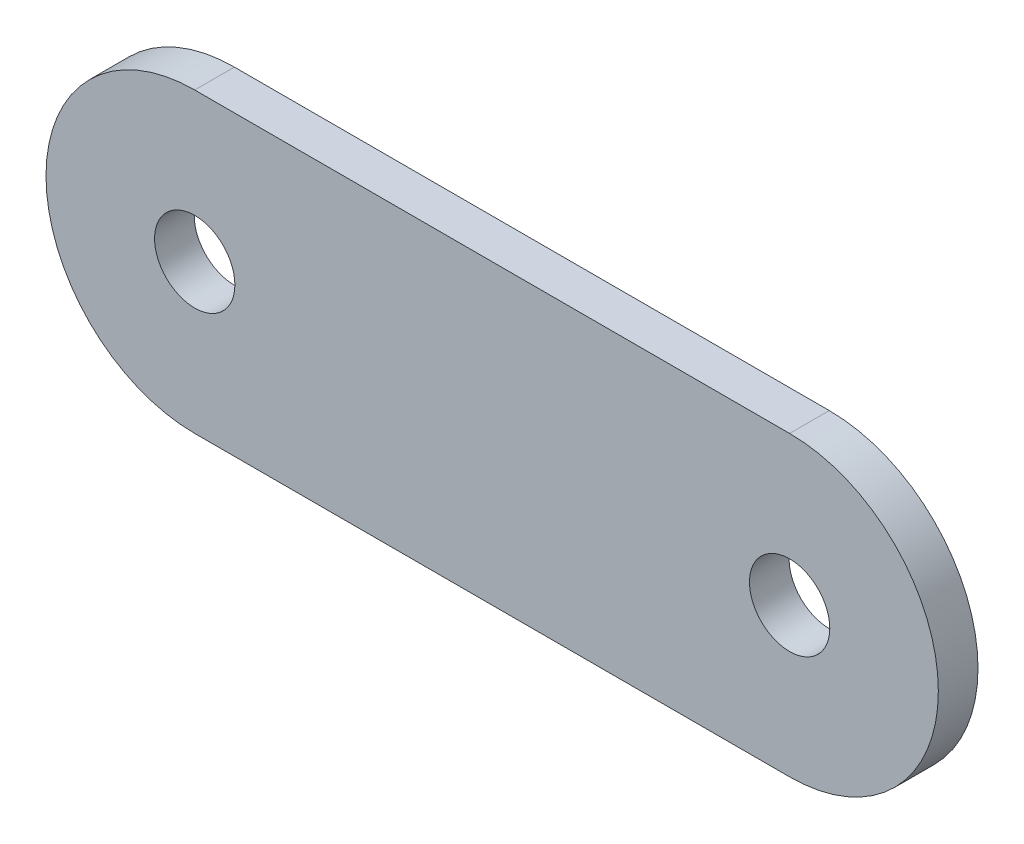
SolidWorks part; units mm, degrees
ref_plane "Front" through (0, 0, 0) normal (0, 0, 1) x (1, 0, 0)
ref_plane "Top" through (0, 0, 0) normal (0, 1, 0) x (1, 0, 0)
ref_plane "Right" through (0, 0, 0) normal (1, 0, 0) x (0, 0, -1)
sketch "Sketch1" plane through (0, 0, 0) normal (0, 0, 1) x (1, 0, 0)
  line L0 (0, 0) -> (15, 0) construction
  line L1 (15, 0) -> (75, 0)
  line L2 (15, 30) -> (75, 30)
  line L3 (0, 0) -> (0, 15) construction
  arc A0 (15, 30) -> (15, 0) centre (15, 15) ccw
  arc A1 (75, 0) -> (75, 30) centre (75, 15) ccw
  circle A4 centre (15, 15) radius 4.05
  circle A5 centre (75, 15) radius 4.05
  point P8 (90, 15)
  dimension "D1" = 30
  dimension "D3" = 8.1
  dimension "D4" = 8.1
  dimension "D2" = 90
extrude "Boss-Extrude1" add sketch "Sketch1" along normal blind 4
